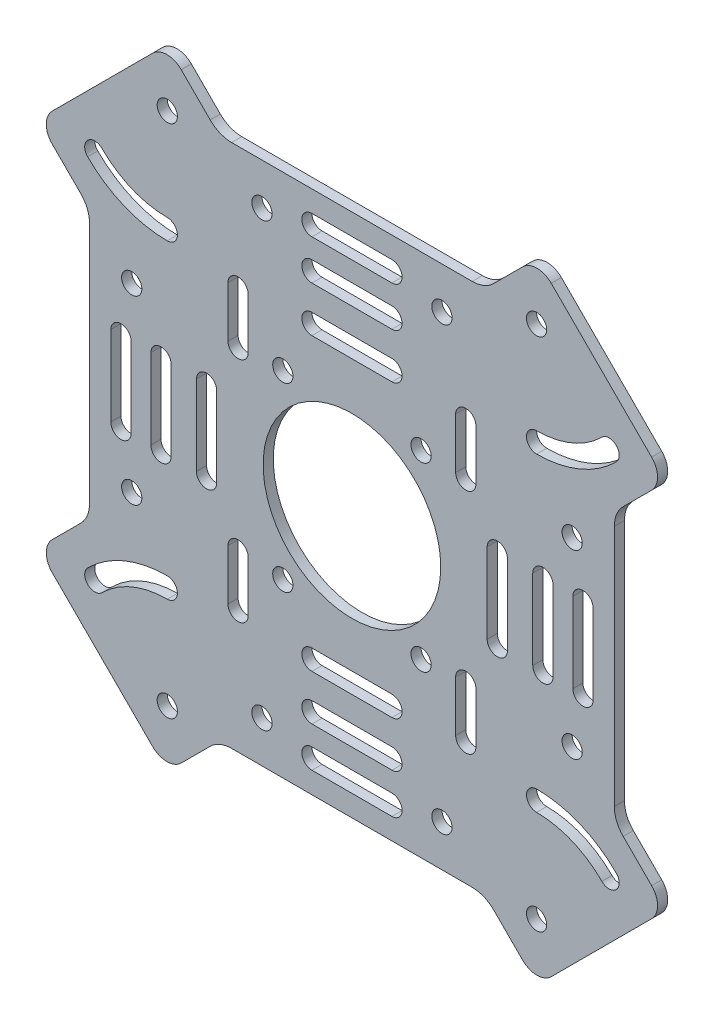
SolidWorks part; units mm, degrees
ref_plane "Alzado" through (0, 0, 0) normal (0, 0, 1) x (1, 0, 0)
ref_plane "Planta" through (0, 0, 0) normal (0, 1, 0) x (1, 0, 0)
ref_plane "Vista lateral" through (0, 0, 0) normal (1, 0, 0) x (0, 0, -1)
sketch "Croquis1" plane through (0, 0, 0) normal (0, 0, 1) x (1, 0, 0)
  line L0 (3840.7928, 1034.1979) -> (3840.7928, 1058.1759)
  line L1 (3788.9428, 1086.0479) -> (3812.7135, 1086.0479)
  line L2 (3828.3372, 1093.5295) -> (3848.1707, 1073.696)
  line L3 (3816.9561, 1087.8053) -> (3822.6803, 1093.5295)
  line L4 (3842.5501, 1062.4186) -> (3848.1707, 1068.0391)
  line L5 (3737.0928, 1034.1979) -> (3737.0928, 1058.1759)
  line L6 (3788.9428, 1086.0479) -> (3765.1721, 1086.0479)
  line L7 (3749.5484, 1093.5295) -> (3729.7149, 1073.696)
  line L8 (3760.9294, 1087.8053) -> (3755.2052, 1093.5295)
  line L9 (3735.3354, 1062.4186) -> (3729.7149, 1068.0391)
  line L10 (3840.7928, 1034.1979) -> (3840.7928, 1010.2199)
  line L11 (3788.9428, 982.3479) -> (3812.7135, 982.3479)
  line L12 (3828.3372, 974.8663) -> (3848.1707, 994.6998)
  line L13 (3816.9561, 980.5905) -> (3822.6803, 974.8663)
  line L14 (3842.5501, 1005.9772) -> (3848.1707, 1000.3567)
  line L15 (3737.0928, 1034.1979) -> (3737.0928, 1010.2199)
  line L16 (3788.9428, 982.3479) -> (3765.1721, 982.3479)
  line L17 (3749.5484, 974.8663) -> (3729.7149, 994.6998)
  line L18 (3760.9294, 980.5905) -> (3755.2052, 974.8663)
  line L19 (3735.3354, 1005.9772) -> (3729.7149, 1000.3567)
  line L20 (3809.4428, 1051.6979) -> (3809.4428, 1061.6979)
  line L21 (3813.4428, 1051.6979) -> (3813.4428, 1061.6979)
  line L22 (3764.4428, 1051.6979) -> (3764.4428, 1061.6979)
  line L23 (3768.4428, 1051.6979) -> (3768.4428, 1061.6979)
  line L24 (3764.4428, 1006.6979) -> (3764.4428, 1016.6979)
  line L25 (3768.4428, 1006.6979) -> (3768.4428, 1016.6979)
  line L26 (3809.4428, 1006.6979) -> (3809.4428, 1016.6979)
  line L27 (3813.4428, 1006.6979) -> (3813.4428, 1016.6979)
  line L28 (3832.5915, 1026.2919) -> (3832.5915, 1042.1038)
  line L29 (3836.5915, 1026.2919) -> (3836.5915, 1042.1038)
  line L30 (3824.6743, 1026.2919) -> (3824.6743, 1042.1038)
  line L31 (3828.6743, 1026.2919) -> (3828.6743, 1042.1038)
  line L32 (3815.6705, 1026.2919) -> (3815.6705, 1042.1038)
  line L33 (3819.6705, 1026.2919) -> (3819.6705, 1042.1038)
  line L34 (3796.8487, 1077.8466) -> (3781.0368, 1077.8466)
  line L35 (3796.8487, 1081.8466) -> (3781.0368, 1081.8466)
  line L36 (3796.8487, 1069.9294) -> (3781.0368, 1069.9294)
  line L37 (3796.8487, 1073.9294) -> (3781.0368, 1073.9294)
  line L38 (3796.8487, 1060.9256) -> (3781.0368, 1060.9256)
  line L39 (3796.8487, 1064.9256) -> (3781.0368, 1064.9256)
  line L40 (3745.2941, 1042.1038) -> (3745.2941, 1026.2919)
  line L41 (3741.2941, 1042.1038) -> (3741.2941, 1026.2919)
  line L42 (3753.2112, 1042.1038) -> (3753.2112, 1026.2919)
  line L43 (3749.2112, 1042.1038) -> (3749.2112, 1026.2919)
  line L44 (3762.2151, 1042.1038) -> (3762.2151, 1026.2919)
  line L45 (3758.2151, 1042.1038) -> (3758.2151, 1026.2919)
  line L46 (3781.0368, 990.5492) -> (3796.8487, 990.5492)
  line L47 (3781.0368, 986.5492) -> (3796.8487, 986.5492)
  line L48 (3781.0368, 998.4664) -> (3796.8487, 998.4664)
  line L49 (3781.0368, 994.4664) -> (3796.8487, 994.4664)
  line L50 (3781.0368, 1007.4702) -> (3796.8487, 1007.4702)
  line L51 (3781.0368, 1003.4702) -> (3796.8487, 1003.4702)
  arc A0 (3842.5501, 1062.4186) -> (3840.7928, 1058.1759) centre (3846.7928, 1058.1759) ccw
  arc A1 (3812.7135, 1086.0479) -> (3816.9561, 1087.8053) centre (3812.7135, 1092.0479) ccw
  arc A2 (3828.3372, 1093.5295) -> (3822.6803, 1093.5295) centre (3825.5088, 1090.701) ccw
  arc A3 (3848.1707, 1068.0391) -> (3848.1707, 1073.696) centre (3845.3423, 1070.8675) ccw
  circle A4 centre (3825.4356, 1085.1173) radius 2
  arc A5 (3841.1728, 1069.3802) -> (3838.3444, 1072.2086) centre (3839.7586, 1070.7944) ccw
  arc A6 (3825.4356, 1066.8616) -> (3825.4356, 1062.8616) centre (3825.4356, 1064.8616) ccw
  arc A7 (3825.4356, 1066.8616) -> (3838.3444, 1072.2086) centre (3825.4356, 1085.1173) ccw
  arc A8 (3825.4356, 1062.8616) -> (3841.1728, 1069.3802) centre (3825.4356, 1085.1173) ccw
  circle A9 centre (3771.1581, 1077.8202) radius 2
  arc A10 (3737.0928, 1058.1759) -> (3735.3354, 1062.4186) centre (3731.0928, 1058.1759) ccw
  arc A11 (3760.9294, 1087.8053) -> (3765.1721, 1086.0479) centre (3765.1721, 1092.0479) ccw
  arc A12 (3755.2052, 1093.5295) -> (3749.5484, 1093.5295) centre (3752.3768, 1090.701) ccw
  arc A13 (3729.7149, 1073.696) -> (3729.7149, 1068.0391) centre (3732.5433, 1070.8675) ccw
  circle A14 centre (3752.4499, 1085.1173) radius 2
  arc A15 (3739.5412, 1072.2086) -> (3736.7128, 1069.3802) centre (3738.127, 1070.7944) ccw
  arc A16 (3752.4499, 1062.8616) -> (3752.4499, 1066.8616) centre (3752.4499, 1064.8616) ccw
  arc A17 (3739.5412, 1072.2086) -> (3752.4499, 1066.8616) centre (3752.4499, 1085.1173) ccw
  arc A18 (3736.7128, 1069.3802) -> (3752.4499, 1062.8616) centre (3752.4499, 1085.1173) ccw
  arc A19 (3840.7928, 1010.2199) -> (3842.5501, 1005.9772) centre (3846.7928, 1010.2199) ccw
  arc A20 (3816.9561, 980.5905) -> (3812.7135, 982.3479) centre (3812.7135, 976.3479) ccw
  arc A21 (3822.6803, 974.8663) -> (3828.3372, 974.8663) centre (3825.5088, 977.6947) ccw
  arc A22 (3848.1707, 994.6998) -> (3848.1707, 1000.3567) centre (3845.3423, 997.5282) ccw
  circle A23 centre (3825.4356, 983.2784) radius 2
  arc A24 (3838.3444, 996.1872) -> (3841.1728, 999.0156) centre (3839.7586, 997.6014) ccw
  arc A25 (3825.4356, 1005.5342) -> (3825.4356, 1001.5342) centre (3825.4356, 1003.5342) ccw
  arc A26 (3838.3444, 996.1872) -> (3825.4356, 1001.5342) centre (3825.4356, 983.2784) ccw
  arc A27 (3841.1728, 999.0156) -> (3825.4356, 1005.5342) centre (3825.4356, 983.2784) ccw
  arc A28 (3735.3354, 1005.9772) -> (3737.0928, 1010.2199) centre (3731.0928, 1010.2199) ccw
  arc A29 (3765.1721, 982.3479) -> (3760.9294, 980.5905) centre (3765.1721, 976.3479) ccw
  arc A30 (3749.5484, 974.8663) -> (3755.2052, 974.8663) centre (3752.3768, 977.6947) ccw
  arc A31 (3729.7149, 1000.3567) -> (3729.7149, 994.6998) centre (3732.5433, 997.5282) ccw
  circle A32 centre (3752.4499, 983.2784) radius 2
  arc A33 (3736.7128, 999.0156) -> (3739.5412, 996.1872) centre (3738.127, 997.6014) ccw
  arc A34 (3752.4499, 1001.5342) -> (3752.4499, 1005.5342) centre (3752.4499, 1003.5342) ccw
  arc A35 (3752.4499, 1001.5342) -> (3739.5412, 996.1872) centre (3752.4499, 983.2784) ccw
  arc A36 (3752.4499, 1005.5342) -> (3736.7128, 999.0156) centre (3752.4499, 983.2784) ccw
  circle A37 centre (3806.7275, 1077.8202) radius 2
  circle A38 centre (3771.1581, 990.5755) radius 2
  circle A39 centre (3806.7275, 990.5755) radius 2
  circle A40 centre (3745.4241, 1052.0863) radius 2
  circle A41 centre (3832.4615, 1052.0863) radius 2
  circle A42 centre (3745.4241, 1016.3095) radius 2
  circle A43 centre (3832.4615, 1016.3095) radius 2
  arc A44 (3813.4428, 1061.6979) -> (3809.4428, 1061.6979) centre (3811.4428, 1061.6979) ccw
  arc A45 (3809.4428, 1051.6979) -> (3813.4428, 1051.6979) centre (3811.4428, 1051.6979) ccw
  arc A46 (3768.4428, 1061.6979) -> (3764.4428, 1061.6979) centre (3766.4428, 1061.6979) ccw
  arc A47 (3764.4428, 1051.6979) -> (3768.4428, 1051.6979) centre (3766.4428, 1051.6979) ccw
  arc A48 (3768.4428, 1016.6979) -> (3764.4428, 1016.6979) centre (3766.4428, 1016.6979) ccw
  arc A49 (3764.4428, 1006.6979) -> (3768.4428, 1006.6979) centre (3766.4428, 1006.6979) ccw
  arc A50 (3813.4428, 1016.6979) -> (3809.4428, 1016.6979) centre (3811.4428, 1016.6979) ccw
  arc A51 (3809.4428, 1006.6979) -> (3813.4428, 1006.6979) centre (3811.4428, 1006.6979) ccw
  arc A52 (3836.5915, 1042.1038) -> (3832.5915, 1042.1038) centre (3834.5915, 1042.1038) ccw
  arc A53 (3832.5915, 1026.2919) -> (3836.5915, 1026.2919) centre (3834.5915, 1026.2919) ccw
  arc A54 (3828.6743, 1042.1038) -> (3824.6743, 1042.1038) centre (3826.6743, 1042.1038) ccw
  arc A55 (3824.6743, 1026.2919) -> (3828.6743, 1026.2919) centre (3826.6743, 1026.2919) ccw
  arc A56 (3819.6705, 1042.1038) -> (3815.6705, 1042.1038) centre (3817.6705, 1042.1038) ccw
  arc A57 (3815.6705, 1026.2919) -> (3819.6705, 1026.2919) centre (3817.6705, 1026.2919) ccw
  circle A58 centre (3788.9428, 1034.0284) radius 17.5507
  arc A59 (3781.0368, 1081.8466) -> (3781.0368, 1077.8466) centre (3781.0368, 1079.8466) ccw
  arc A60 (3796.8487, 1077.8466) -> (3796.8487, 1081.8466) centre (3796.8487, 1079.8466) ccw
  arc A61 (3781.0368, 1073.9294) -> (3781.0368, 1069.9294) centre (3781.0368, 1071.9294) ccw
  arc A62 (3796.8487, 1069.9294) -> (3796.8487, 1073.9294) centre (3796.8487, 1071.9294) ccw
  arc A63 (3781.0368, 1064.9256) -> (3781.0368, 1060.9256) centre (3781.0368, 1062.9256) ccw
  arc A64 (3796.8487, 1060.9256) -> (3796.8487, 1064.9256) centre (3796.8487, 1062.9256) ccw
  arc A65 (3741.2941, 1026.2919) -> (3745.2941, 1026.2919) centre (3743.2941, 1026.2919) ccw
  arc A66 (3745.2941, 1042.1038) -> (3741.2941, 1042.1038) centre (3743.2941, 1042.1038) ccw
  arc A67 (3749.2112, 1026.2919) -> (3753.2112, 1026.2919) centre (3751.2112, 1026.2919) ccw
  arc A68 (3753.2112, 1042.1038) -> (3749.2112, 1042.1038) centre (3751.2112, 1042.1038) ccw
  arc A69 (3758.2151, 1026.2919) -> (3762.2151, 1026.2919) centre (3760.2151, 1026.2919) ccw
  arc A70 (3762.2151, 1042.1038) -> (3758.2151, 1042.1038) centre (3760.2151, 1042.1038) ccw
  arc A71 (3796.8487, 986.5492) -> (3796.8487, 990.5492) centre (3796.8487, 988.5492) ccw
  arc A72 (3781.0368, 990.5492) -> (3781.0368, 986.5492) centre (3781.0368, 988.5492) ccw
  arc A73 (3796.8487, 994.4664) -> (3796.8487, 998.4664) centre (3796.8487, 996.4664) ccw
  arc A74 (3781.0368, 998.4664) -> (3781.0368, 994.4664) centre (3781.0368, 996.4664) ccw
  arc A75 (3796.8487, 1003.4702) -> (3796.8487, 1007.4702) centre (3796.8487, 1005.4702) ccw
  arc A76 (3781.0368, 1007.4702) -> (3781.0368, 1003.4702) centre (3781.0368, 1005.4702) ccw
  circle A77 centre (3775.2829, 1052.0863) radius 2
  circle A78 centre (3802.6027, 1052.0863) radius 2
  circle A79 centre (3775.2829, 1016.3095) radius 2
  circle A80 centre (3802.6027, 1016.3095) radius 2
extrude "Saliente-Extruir1" add sketch "Croquis1" along normal blind 2
